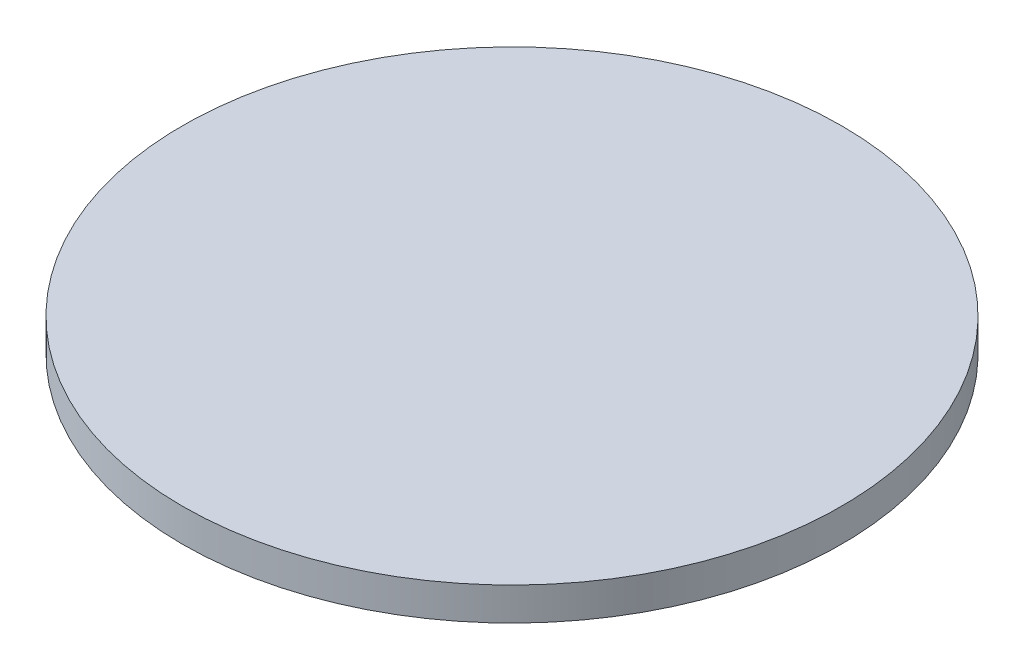
SolidWorks part; units mm, degrees
ref_plane "Front Plane" through (0, 0, 0) normal (0, 0, 1) x (1, 0, 0)
ref_plane "Top Plane" through (0, 0, 0) normal (0, 1, 0) x (1, 0, 0)
ref_plane "Right Plane" through (0, 0, 0) normal (1, 0, 0) x (0, 0, -1)
other "Configuration Table"
sketch "Sketch1" plane through (0, 0, 0) normal (0, 1, 0) x (1, 0, 0)
  circle A0 centre (0, 0) radius 30
extrude "KOLA330_alt_bilezik_D60" add sketch "Sketch1" along normal blind 3 separate body
